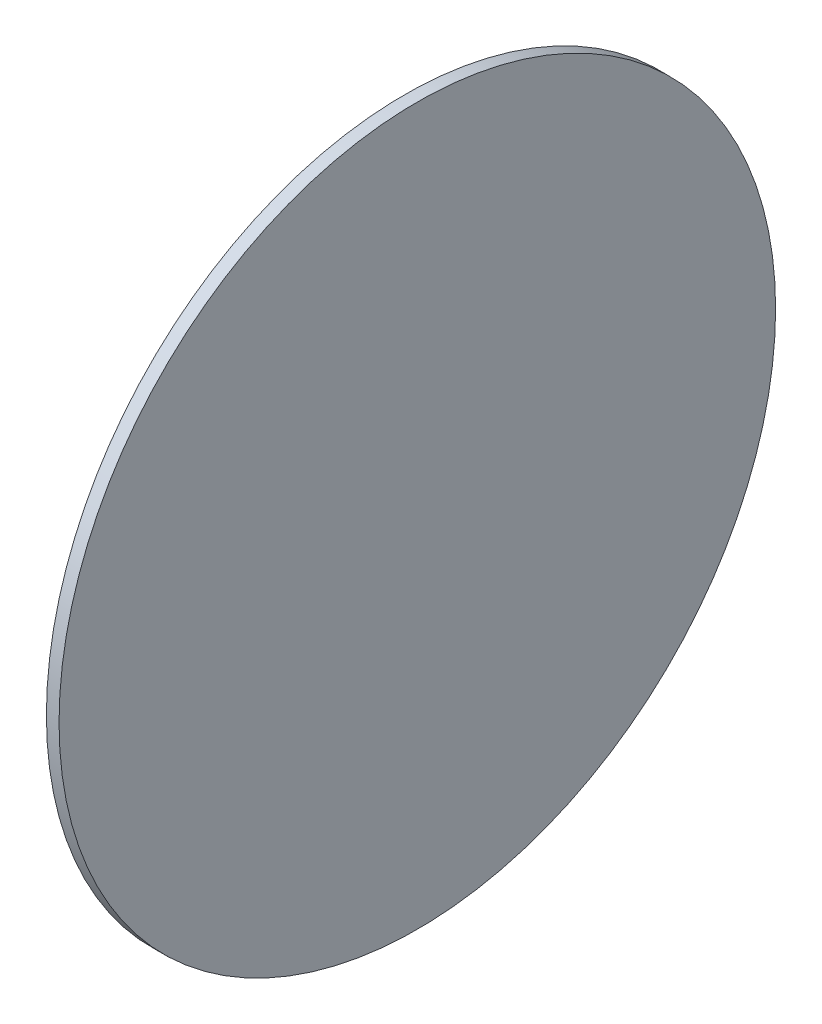
SolidWorks part; units mm, degrees
ref_plane "Ebene vorne" through (0, 0, 0) normal (0, 0, 1) x (1, 0, 0)
ref_plane "Ebene oben" through (0, 0, 0) normal (0, 1, 0) x (1, 0, 0)
ref_plane "Ebene rechts" through (0, 0, 0) normal (1, 0, 0) x (0, 0, -1)
sketch "Skizze1" plane through (0, 0, 0) normal (1, 0, 0) x (0, 0, -1)
  circle A0 centre (0, 0) radius 51
  dimension "D1" = 102
extrude "Aufsatz-Linear austragen1" add sketch "Skizze1" along normal blind 1.8
